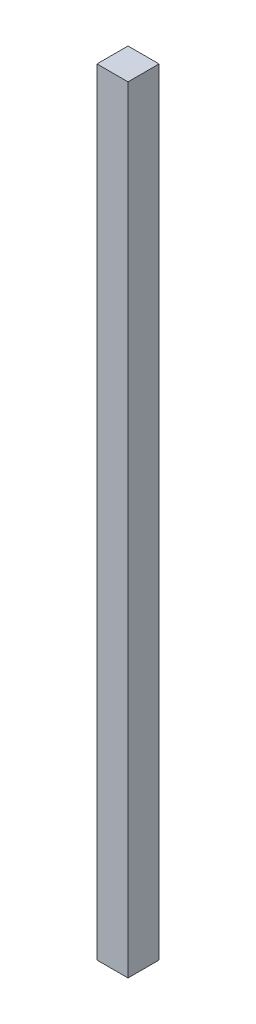
SolidWorks part; units mm, degrees
material "Cast Alloy Steel"
ref_plane "Front Plane" through (0, 0, 0) normal (0, 0, 1) x (1, 0, 0)
ref_plane "Top Plane" through (0, 0, 0) normal (0, 1, 0) x (1, 0, 0)
ref_plane "Right Plane" through (0, 0, 0) normal (1, 0, 0) x (0, 0, -1)
sketch "Sketch1" plane through (0, 0, 0) normal (0, 1, 0) x (1, 0, 0)
  line L1 (10, -10) -> (-10, -10)
  line L2 (10, -10) -> (10, 10)
  line L3 (10, 10) -> (-10, 10)
  line L4 (-10, -10) -> (-10, 10)
  line L5 (10, -10) -> (-10, 10) construction
  line L6 (10, 10) -> (-10, -10) construction
  point P0 (0, 0)
  dimension "D1" = 20
  dimension "D2" = 20
extrude "Boss-Extrude1" add sketch "Sketch1" along normal mid plane 500
